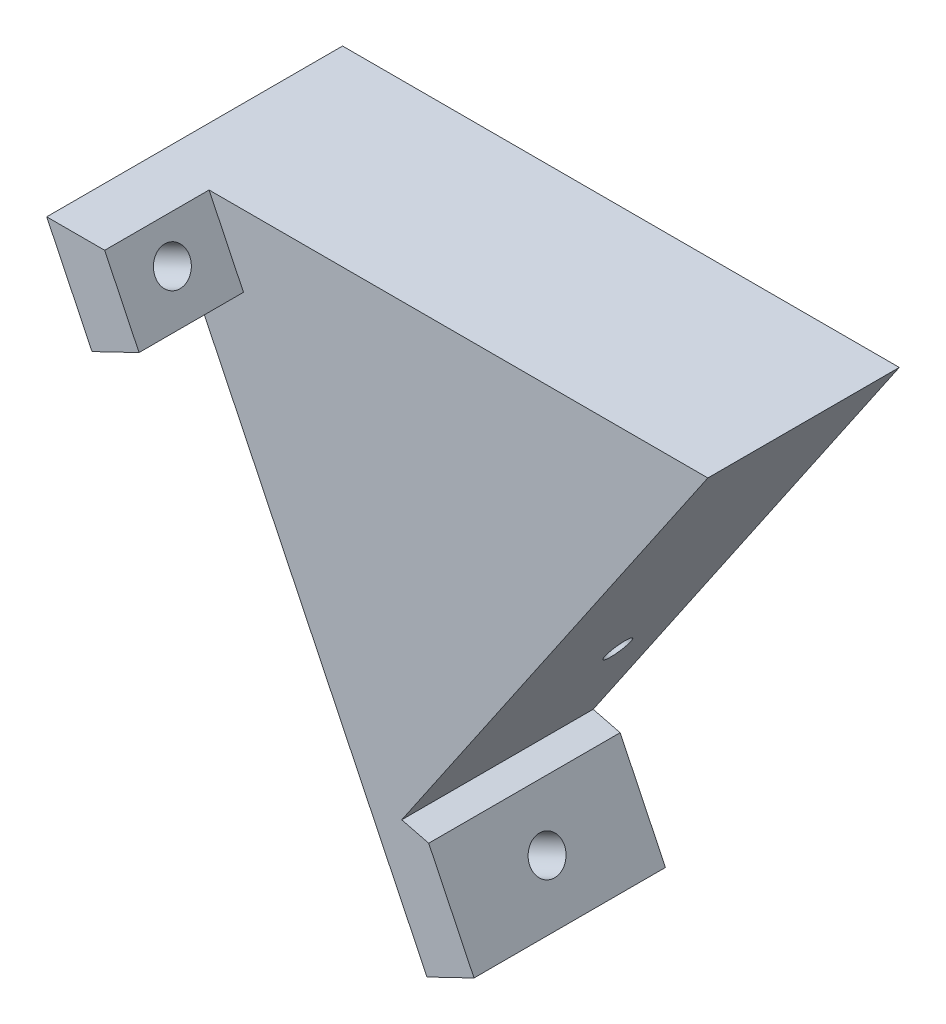
SolidWorks part; units mm, degrees
material "ABS"
ref_plane "Front Plane" through (0, 0, 0) normal (0, 0, 1) x (1, 0, 0)
ref_plane "Top Plane" through (0, 0, 0) normal (0, 1, 0) x (1, 0, 0)
ref_plane "Right Plane" through (0, 0, 0) normal (1, 0, 0) x (0, 0, -1)
sketch "Sketch1" plane through (0, 0, 0) normal (0, 0, 1) x (1, 0, 0)
  line L0 (-36.2386, 24.2413) -> (-9.7428, -30.7587)
  line L1 (-9.7428, -30.7587) -> (27.7446, 24.2413)
  line L2 (27.7446, 24.2413) -> (-36.2386, 24.2413)
  dimension "D1" = 55
  dimension "D2" = 55
  dimension "D3" = 60
extrude "Boss-Extrude1" add sketch "Sketch1" along normal blind 22
sketch "Sketch6" plane through (-19.9343, -9.6032, 0) normal (-0.9009, -0.434, 0) x (0, 0, 1)
  line L0 (22, 37.5671) -> (22, -23.4823) construction
  line L1 (34, 37.5671) -> (22, 37.5671)
  line L2 (34, 37.5671) -> (34, 25.5671)
  line L3 (34, 25.5671) -> (22, 25.5671)
  line L4 (22, 37.5671) -> (22, 25.5671)
  line L5 (0, -23.4823) -> (22, -23.4823)
  line L6 (0, -23.4823) -> (0, -35.4823)
  line L7 (0, -35.4823) -> (22, -35.4823)
  line L8 (22, -23.4823) -> (22, -35.4823)
  line L9 (22, 37.5671) -> (0, 37.5671) construction
  dimension "D1" = 12
  dimension "D2" = 12
  dimension "D3" = 0
  dimension "D4" = 12
  dimension "D5" = 0
  dimension "D6" = 0
extrude "Boss-Extrude4" add sketch "Sketch6" against normal blind 6
sketch "Sketch8" plane through (0, 0, 0) normal (0, 0, -1) x (-1, 0, 0)
  line L0 (9.7428, -30.7587) -> (4.3373, -28.1546)
  line L1 (4.3373, -28.1546) -> (7.4364, -27.3748)
  line L2 (9.7428, -30.7587) -> (-27.7446, 24.2413) construction
  line L3 (7.4364, -27.3748) -> (9.7428, -30.7587)
extrude "Boss-Extrude5" add sketch "Sketch8" against normal up to vertex (22 mm away) up to point (27.7446, 24.2413, 22)
sketch "Sketch9" plane through (-14.5288, -6.9992, 0) normal (0.9009, 0.434, 0) x (0, 0, -1)
  line L2 (-22, 25.5671) -> (-34, 25.5671) construction
  line L3 (0, -35.4823) -> (-22, -35.4823) construction
  line L4 (-22, -35.4823) -> (-22, -23.4823) construction
  circle A0 centre (-28, 30.5671) radius 2
  circle A1 centre (-11, -29.4823) radius 2
  point P9 (-28, 25.5671)
  point P12 (-11, -35.4823)
  point P15 (-22, -29.4823)
  dimension "D1" = 4
  dimension "D2" = 4
  dimension "D3" = 5
  dimension "D4" = 0
  dimension "D5" = 0
  dimension "D6" = 0
extrude "Cut-Extrude9" cut sketch "Sketch9" against normal blind 6
sketch "Sketch10" plane through (7.6623, -5.2226, 0) normal (0.8263, -0.5632, 0) x (0, 0, -1)
  line L0 (-22, 35.657) -> (0, 35.657) construction
  line L1 (0, -26.8085) -> (0, 35.657) construction
  circle A0 centre (-7, -9.343) radius 1.5
  dimension "D1" = 3
  dimension "D3" = 7
  dimension "D2" = 45
extrude "Cut-Extrude10" cut sketch "Sketch10" against normal blind 36
sketch "Sketch12" plane through (0, 0, 22) normal (0, 0, -1) x (-1, 0, 0)
  line L0 (30.8332, 26.8454) -> (29.5787, 24.2413)
  line L1 (29.5787, 24.2413) -> (36.2386, 24.2413)
  line L2 (36.2386, 24.2413) -> (30.8332, 26.8454)
extrude "Cut-Extrude11" cut sketch "Sketch12" against normal blind 20
